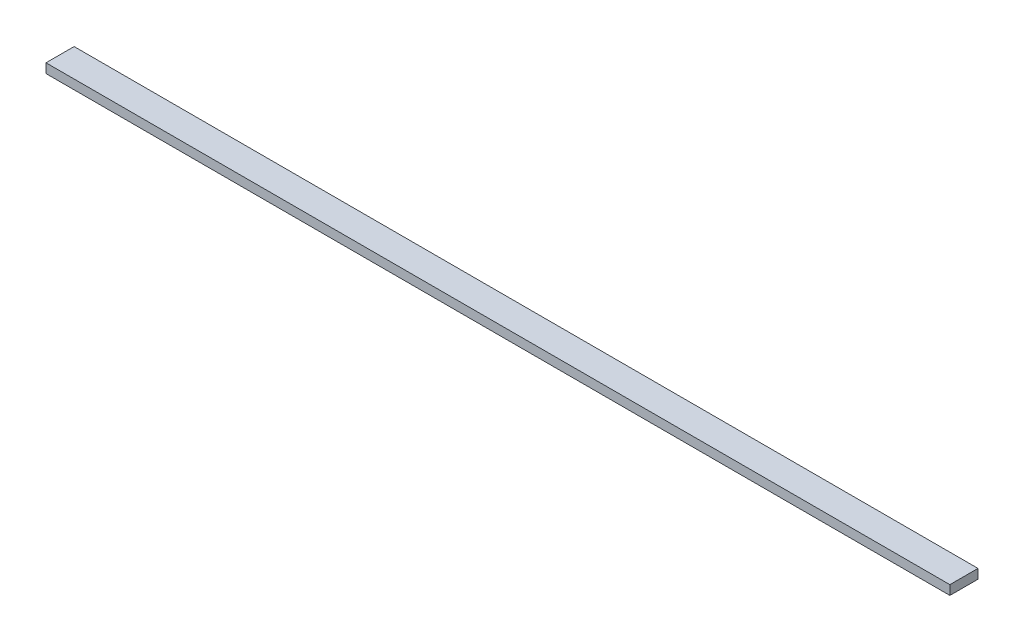
SolidWorks part; units mm, degrees
material "Acrylic (Medium-high impact)"
ref_plane "Front Plane" through (0, 0, 0) normal (0, 0, 1) x (1, 0, 0)
ref_plane "Top Plane" through (0, 0, 0) normal (0, 1, 0) x (1, 0, 0)
ref_plane "Right Plane" through (0, 0, 0) normal (1, 0, 0) x (0, 0, -1)
sketch "Sketch1" plane through (0, 0, 0) normal (0, 1, 0) x (1, 0, 0)
  line L1 (-306.1398, -9.525) -> (306.1399, -9.525)
  line L2 (-306.1398, -9.525) -> (-306.1398, 9.525)
  line L3 (-306.1398, 9.525) -> (306.1399, 9.525)
  line L4 (306.1399, -9.525) -> (306.1399, 9.525)
  line L5 (-306.1398, -9.525) -> (306.1399, 9.525) construction
  line L6 (-306.1398, 9.525) -> (306.1399, -9.525) construction
  point P0 (0, 0)
  dimension "D1" = 19.05
  dimension "D2" = 612.2797
extrude "Boss-Extrude1" add sketch "Sketch1" along normal blind 6.35
